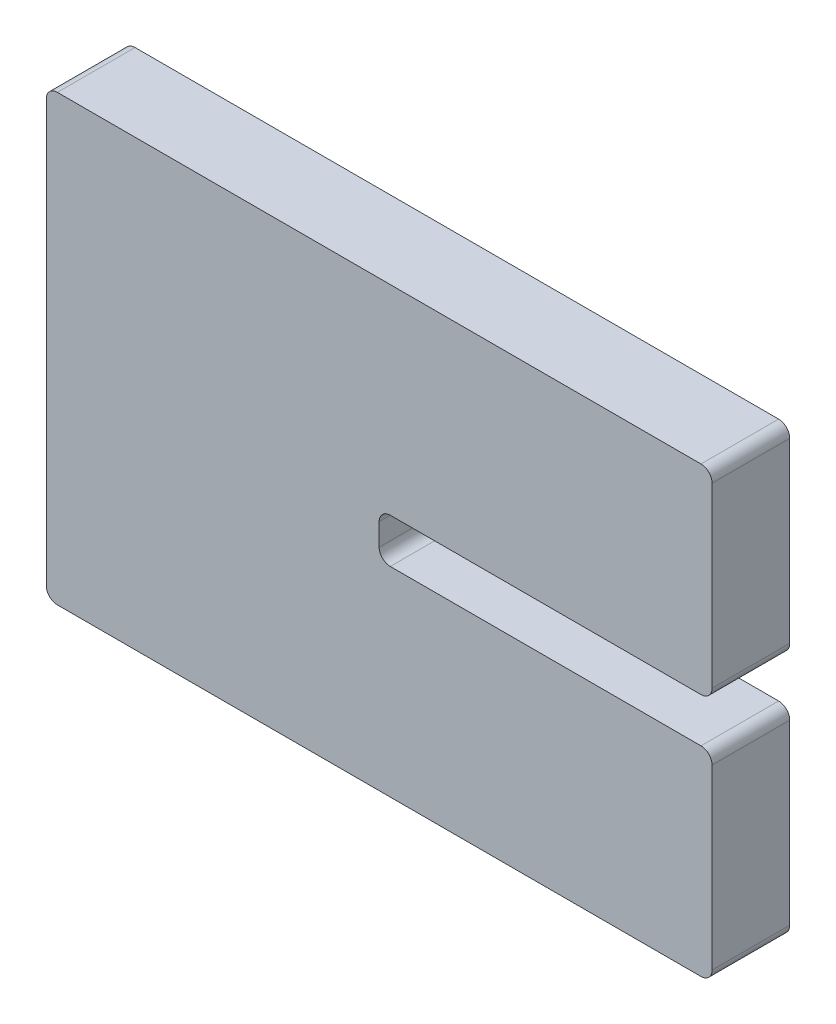
SolidWorks part; units mm, degrees
ref_plane "Front Plane" through (0, 0, 0) normal (0, 0, 1) x (1, 0, 0)
ref_plane "Top Plane" through (0, 0, 0) normal (0, 1, 0) x (1, 0, 0)
ref_plane "Right Plane" through (0, 0, 0) normal (1, 0, 0) x (0, 0, -1)
sketch "Sketch1" plane through (0, 0, 0) normal (0, 0, 1) x (1, 0, 0)
  line L0 (15, -1) -> (15, -10)
  line L1 (-15, 10) -> (15, 10)
  line L2 (-15, 10) -> (-15, -10)
  line L3 (-15, -10) -> (15, -10)
  line L4 (15, 10) -> (15, 1)
  line L5 (-15, 10) -> (15, -10) construction
  line L6 (-15, -10) -> (15, 10) construction
  line L7 (0, -1) -> (15, -1)
  line L8 (0, -1) -> (0, 1)
  line L9 (0, 1) -> (15, 1)
  point P0 (0, 0)
  point P10 (0, 0)
  dimension "D1" = 30
  dimension "D2" = 20
  dimension "D3" = 2
extrude "Boss-Extrude1" add sketch "Sketch1" along normal blind 3.5
fillet "Fillet1" radius 0.5 8 edges at (0, -1, 1.75) (0, 1, 1.75) (15, 10, 1.75) (15, -1, 1.75) (15, 1, 1.75) (15, -10, 1.75) (-15, -10, 1.75) (-15, 10, 1.75)
